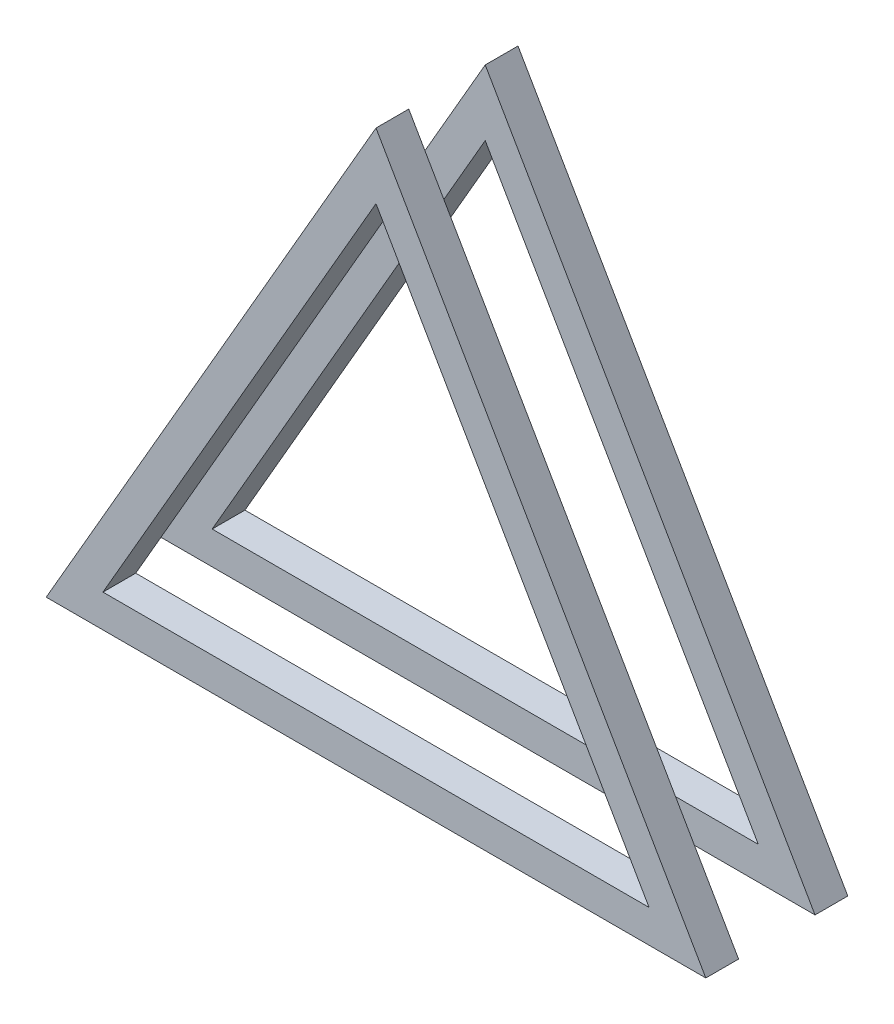
SolidWorks part; units mm, degrees
ref_plane "Front" through (0, 0, 0) normal (0, 0, 1) x (1, 0, 0)
ref_plane "Top" through (0, 0, 0) normal (0, 1, 0) x (1, 0, 0)
ref_plane "Right" through (0, 0, 0) normal (1, 0, 0) x (0, 0, -1)
sketch "Sketch1" plane through (0, 0, 0) normal (0, 0, 1) x (1, 0, 0)
  line L0 (0, 0) -> (50, 0)
  line L1 (50, 0) -> (25, 43.3013)
  line L2 (25, 43.3013) -> (0, 0)
  line L3 (55.1962, -3) -> (25, 49.3013)
  line L4 (25, 49.3013) -> (-5.1962, -3)
  line L5 (-5.1962, -3) -> (55.1962, -3)
  dimension "D1" = 50
  dimension "D2" = 50
  dimension "D3" = 50
  dimension "D4" = 3
extrude "Boss-Extrude2" add sketch "Sketch1" along normal blind 3
ref_plane "Plane1" through (0, 0, -10) normal (0, 0, 1) x (1, 0, 0)
sketch "Sketch2" plane through (0, 0, -10) normal (0, 0, 1) x (1, 0, 0)
  line L0 (0, 0) -> (50, 0)
  line L1 (50, 0) -> (25, 43.3013)
  line L2 (25, 43.3013) -> (0, 0)
  line L3 (55.1962, -3) -> (25, 49.3013)
  line L4 (25, 49.3013) -> (-5.1962, -3)
  line L5 (-5.1962, -3) -> (55.1962, -3)
  dimension "D1" = 50
  dimension "D2" = 50
  dimension "D3" = 50
  dimension "D4" = 3
extrude "Boss-Extrude3" add sketch "Sketch2" along normal blind 3 separate body
